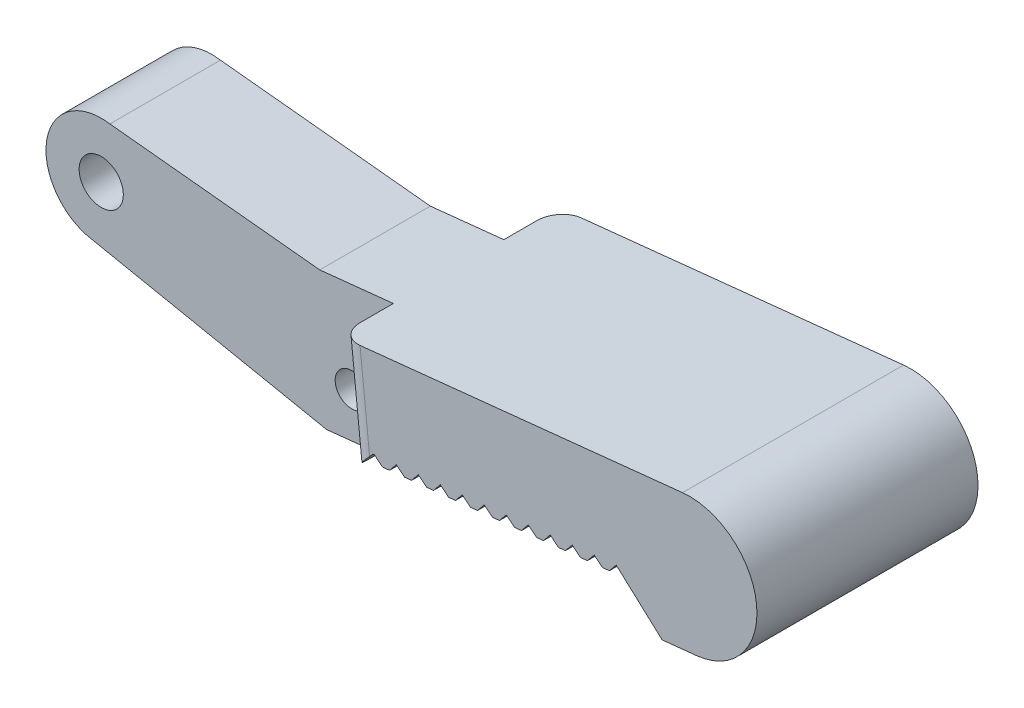
SolidWorks part; units mm, degrees
ref_plane "Front Plane" through (0, 0, 0) normal (0, 0, 1) x (1, 0, 0)
ref_plane "Top Plane" through (0, 0, 0) normal (0, 1, 0) x (1, 0, 0)
ref_plane "Right Plane" through (0, 0, 0) normal (1, 0, 0) x (0, 0, -1)
ref_plane "Plane1" through (0, 0, 73) normal (0, 0, 1) x (1, 0, 0)
sketch "Sketch1" plane through (0, 0, 73) normal (0, 0, 1) x (1, 0, 0)
  line L0 (47.1499, 28.3134) -> (52.6195, 34.3226)
  line L1 (52.6195, 34.3226) -> (64.7596, 24.4813)
  line L2 (64.7596, 24.4813) -> (74.5552, 36.5649)
  line L3 (74.5552, 36.5649) -> (78.7165, 32.7772)
  line L4 (78.7165, 32.7772) -> (81.8273, 33.1025)
  line L5 (80.5584, 45.2363) -> (42.7381, 41.2812)
  line L6 (42.7381, 41.2812) -> (23.7504, 43.2229)
  line L7 (22.1809, 33.3468) -> (47.1499, 28.3134)
  arc A0 (81.8273, 33.1025) -> (80.5584, 45.2363) centre (81.1929, 39.1694) ccw
  arc A1 (23.7504, 43.2229) -> (22.1809, 33.3468) centre (22.9657, 38.2849) ccw
extrude "Boss-Extrude1" add sketch "Sketch1" against normal blind 10
sketch "Sketch2" plane through (0, 0, 73) normal (0, 0, 1) x (1, 0, 0)
  line L0 (64.7596, 24.4813) -> (52.6195, 34.3226)
  line L1 (52.6195, 34.3226) -> (50.4436, 31.932)
  line L2 (50.4436, 31.932) -> (49.3931, 41.9772)
  line L3 (49.3931, 41.9772) -> (80.5584, 45.2363)
  line L4 (81.8273, 33.1025) -> (78.7165, 32.7772)
  line L5 (78.7165, 32.7772) -> (74.5552, 36.5649)
  line L6 (74.5552, 36.5649) -> (64.7596, 24.4813)
  arc A0 (80.5584, 45.2363) -> (81.8273, 33.1025) centre (81.1929, 39.1694) cw
extrude "Boss-Extrude2" add sketch "Sketch2" along normal blind 5
sketch "Sketch3" plane through (0, 0, 63) normal (0, 0, -1) x (-1, 0, 0)
  line L0 (-64.7596, 24.4813) -> (-74.5552, 36.5649)
  line L1 (-74.5552, 36.5649) -> (-78.7165, 32.7772)
  line L2 (-78.7165, 32.7772) -> (-81.8273, 33.1025)
  line L3 (-80.5584, 45.2363) -> (-49.3931, 41.9772)
  line L4 (-49.3931, 41.9772) -> (-50.4436, 31.932)
  line L5 (-50.4436, 31.932) -> (-52.6195, 34.3226)
  line L6 (-52.6195, 34.3226) -> (-64.7596, 24.4813)
  arc A0 (-81.8273, 33.1025) -> (-80.5584, 45.2363) centre (-81.1929, 39.1694) cw
extrude "Boss-Extrude3" add sketch "Sketch3" along normal blind 5
sketch "Sketch4" plane through (0, 0, 58) normal (0, 0, -1) x (-1, 0, 0)
  line L0 (-64.7596, 24.4813) -> (-53.7737, 33.3869)
  line L1 (-53.7737, 33.3869) -> (-54.6636, 34.4847)
  line L2 (-54.6636, 34.4847) -> (-65.6587, 25.5905)
  line L3 (-65.6587, 25.5905) -> (-64.7596, 24.4813)
extrude "Cut-Extrude1" cut sketch "Sketch4" against normal through all
sketch "Sketch5" plane through (0, 0, 58) normal (0, 0, -1) x (-1, 0, 0)
  line L0 (-55.7631, 33.5953) -> (-56.6528, 34.6928)
  line L1 (-56.6528, 34.6928) -> (-66.5484, 26.6879)
  line L2 (-66.5484, 26.6879) -> (-65.6587, 25.5905)
  line L3 (-65.6587, 25.5905) -> (-55.7631, 33.5953)
extrude "Cut-Extrude2" cut sketch "Sketch5" against normal through all
sketch "Sketch6" plane through (0, 0, 58) normal (0, 0, -1) x (-1, 0, 0)
  line L0 (-57.7523, 33.8033) -> (-58.6419, 34.9008)
  line L1 (-58.6419, 34.9008) -> (-67.438, 27.7854)
  line L2 (-67.438, 27.7854) -> (-66.5484, 26.6879)
  line L3 (-66.5484, 26.6879) -> (-57.7523, 33.8033)
extrude "Cut-Extrude3" cut sketch "Sketch6" against normal through all
sketch "Sketch7" plane through (0, 0, 58) normal (0, 0, -1) x (-1, 0, 0)
  line L0 (-59.7415, 34.0113) -> (-60.6311, 35.1088)
  line L1 (-60.6311, 35.1088) -> (-68.3277, 28.8828)
  line L2 (-68.3277, 28.8828) -> (-67.438, 27.7854)
  line L3 (-67.438, 27.7854) -> (-59.7415, 34.0113)
extrude "Cut-Extrude4" cut sketch "Sketch7" against normal through all
sketch "Sketch8" plane through (0, 0, 58) normal (0, 0, -1) x (-1, 0, 0)
  line L0 (-61.7306, 34.2194) -> (-62.6202, 35.3168)
  line L1 (-62.6202, 35.3168) -> (-69.2173, 29.9803)
  line L2 (-69.2173, 29.9803) -> (-68.3277, 28.8828)
  line L3 (-68.3277, 28.8828) -> (-61.7306, 34.2194)
extrude "Cut-Extrude5" cut sketch "Sketch8" against normal through all
sketch "Sketch9" plane through (0, 0, 58) normal (0, 0, -1) x (-1, 0, 0)
  line L0 (-63.7198, 34.4274) -> (-64.6094, 35.5248)
  line L1 (-64.6094, 35.5248) -> (-70.107, 31.0777)
  line L2 (-70.107, 31.0777) -> (-69.2173, 29.9803)
  line L3 (-69.2173, 29.9803) -> (-63.7198, 34.4274)
extrude "Cut-Extrude6" cut sketch "Sketch9" against normal through all
sketch "Sketch10" plane through (0, 0, 58) normal (0, 0, -1) x (-1, 0, 0)
  line L0 (-65.7089, 34.6354) -> (-66.5986, 35.7328)
  line L1 (-66.5986, 35.7328) -> (-70.9966, 32.1751)
  line L2 (-70.9966, 32.1751) -> (-70.107, 31.0777)
  line L3 (-70.107, 31.0777) -> (-65.7089, 34.6354)
extrude "Cut-Extrude7" cut sketch "Sketch10" against normal through all
sketch "Sketch11" plane through (0, 0, 58) normal (0, 0, -1) x (-1, 0, 0)
  line L0 (-70.9966, 32.1751) -> (-67.6977, 34.8437)
  line L1 (-67.6977, 34.8437) -> (-68.5891, 35.941)
  line L2 (-68.5891, 35.941) -> (-71.8841, 33.2699)
  line L3 (-71.8841, 33.2699) -> (-70.9966, 32.1751)
extrude "Cut-Extrude8" cut sketch "Sketch11" against normal through all
sketch "Sketch12" plane through (0, 0, 58) normal (0, 0, -1) x (-1, 0, 0)
  line L0 (-69.6869, 35.0511) -> (-70.5769, 36.1489)
  line L1 (-70.5769, 36.1489) -> (-72.7759, 34.37)
  line L2 (-72.7759, 34.37) -> (-71.8841, 33.2699)
  line L3 (-71.8841, 33.2699) -> (-69.6869, 35.0511)
extrude "Cut-Extrude9" cut sketch "Sketch12" against normal through all
sketch "Sketch13" plane through (0, 0, 58) normal (0, 0, -1) x (-1, 0, 0)
  line L0 (-71.6764, 35.2594) -> (-72.566, 36.3569)
  line L1 (-72.566, 36.3569) -> (-73.6655, 35.4675)
  line L2 (-73.6655, 35.4675) -> (-72.7759, 34.37)
  line L3 (-72.7759, 34.37) -> (-71.6764, 35.2594)
extrude "Cut-Extrude10" cut sketch "Sketch13" against normal through all
hole_wizard "Ø3.0 (3) Diameter Hole1" positions "Sketch15" profile "Sketch14" hole size "Ø3.0" standard "ANSI Metric"
sketch "Sketch15" plane through (0, 0, 73) normal (0, 0, 1) x (1, 0, 0)
  point P0 (45.6293, 33.3389)
sketch "Sketch14" plane through (45.6293, 33.3389, 73) normal (1, 0, 0) x (0, -1, 0)
  line L0 (0, 0) -> (0, 15)
  line L1 (0, 15) -> (1.5, 15)
  line L2 (1.5, 15) -> (1.5, 0)
  line L5 (1.5, 0) -> (0, 0)
  line L11 (0, -6.35) -> (0, 107.95) construction
  dimension "Thru Hole Dia." = 3
  dimension "Thru Hole Depth" = 15
hole_wizard "Ø4.0 (4) Diameter Hole1" positions "Sketch17" profile "Sketch16" hole size "Ø4.0" standard "ANSI Metric"
sketch "Sketch17" plane through (0, 0, 73) normal (0, 0, 1) x (1, 0, 0)
  point P0 (22.9657, 38.2849)
sketch "Sketch16" plane through (22.9657, 38.2849, 73) normal (1, 0, 0) x (0, -1, 0)
  line L0 (0, 0) -> (0, 15)
  line L1 (0, 15) -> (2, 15)
  line L2 (2, 15) -> (2, 0)
  line L5 (2, 0) -> (0, 0)
  line L11 (0, -6.35) -> (0, 107.95) construction
  dimension "Thru Hole Dia." = 4
  dimension "Thru Hole Depth" = 15
chamfer "Chamfer1" distance 0.4477 angle 45 10 edges at (61.7306, 34.2194, 68) (73.6655, 35.4675, 68) (57.7523, 33.8033, 68) (53.7737, 33.3869, 68) (63.7198, 34.4274, 68) (71.6764, 35.2594, 68) (59.7415, 34.0113, 68) (69.6869, 35.0511, 68) (55.7631, 33.5953, 68) (65.7089, 34.6354, 68)
chamfer "Chamfer2" distance 0.4477 angle 44.94 1 edges at (67.6977, 34.8437, 68)
chamfer "Chamfer3" distance 1.7376 angle 41.721 1 edges at (47.1499, 28.3134, 68)
chamfer "Chamfer4" distance 0.0771 angle 41.721 1 edges at (52.6195, 34.3226, 68)
fillet "Fillet1" radius 2 2 edges at (49.9183, 36.9546, 58) (49.9183, 36.9546, 78)
